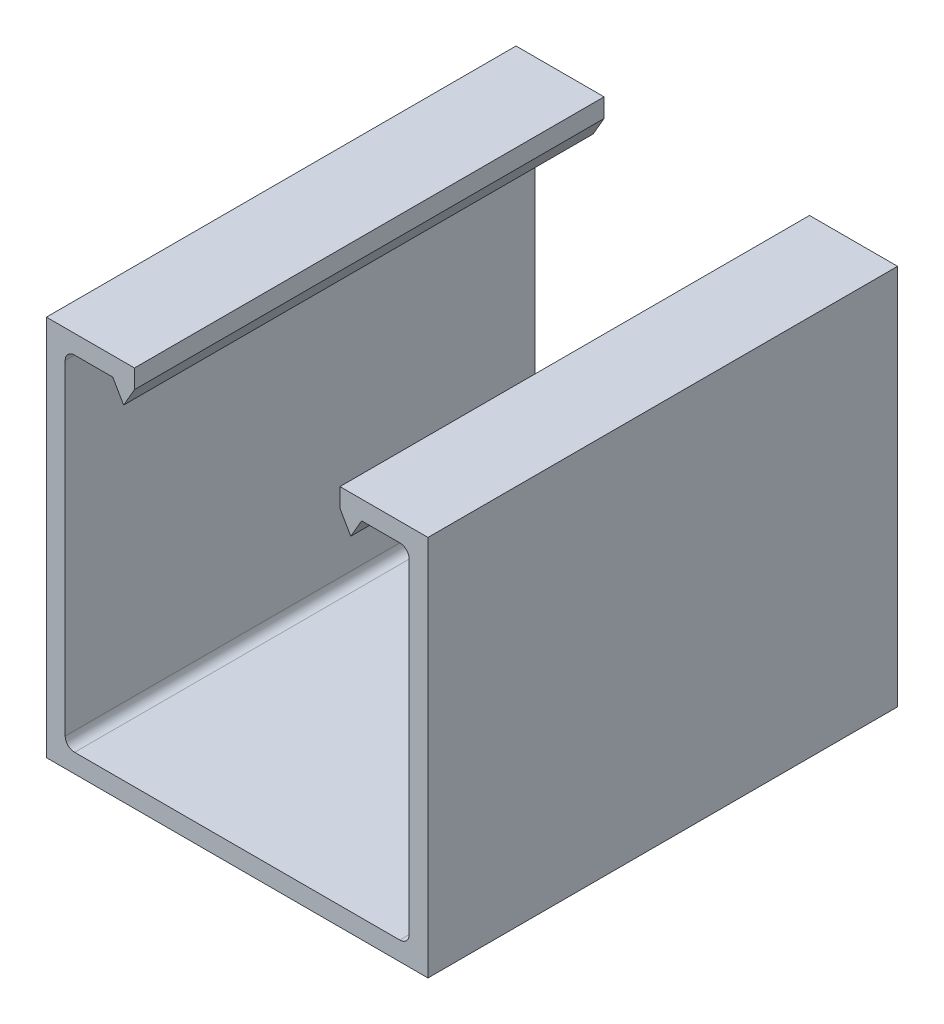
SolidWorks part; units mm, degrees
ref_plane "Plane1" through (0, 0, 0) normal (0, 0, 1) x (1, 0, 0)
ref_plane "Plane2" through (0, 0, 0) normal (0, 1, 0) x (1, 0, 0)
ref_plane "Plane3" through (0, 0, 0) normal (1, 0, 0) x (0, 0, -1)
sketch "Sketch1" plane through (0, 0, 0) normal (0, 0, 1) x (1, 0, 0)
  line L0 (-5.5563, 10.3187) -> (-10.3188, 10.3187)
  line L1 (-10.3188, 10.3187) -> (-10.3187, -10.3187)
  line L2 (-10.3187, -10.3187) -> (10.3188, -10.3187)
  line L3 (10.3188, -10.3187) -> (10.3187, 10.3188)
  line L4 (10.3187, 10.3188) -> (5.5562, 10.3188)
  line L5 (8.7948, 9.3028) -> (6.7294, 9.3028)
  line L6 (9.3028, -8.7948) -> (9.3027, 8.7948)
  line L7 (-8.7947, -9.3028) -> (8.7948, -9.3028)
  line L8 (-9.3027, 8.7947) -> (-9.3027, -8.7948)
  line L9 (-6.7294, 9.3027) -> (-8.7948, 9.3027)
  line L10 (6.7294, 9.3028) -> (6.1428, 8.2868)
  line L11 (6.1428, 8.2868) -> (5.5562, 9.3028)
  line L12 (5.5562, 9.3028) -> (5.5562, 10.3188)
  line L13 (-6.7294, 9.3027) -> (-6.1428, 8.2868)
  line L14 (-6.1428, 8.2868) -> (-5.5563, 9.3027)
  line L15 (-5.5563, 9.3027) -> (-5.5563, 10.3187)
  arc A0 (-9.3027, -8.7948) -> (-8.7947, -9.3028) centre (-8.7947, -8.7948) ccw
  arc A1 (-8.7948, 9.3027) -> (-9.3027, 8.7947) centre (-8.7948, 8.7947) ccw
  arc A2 (9.3027, 8.7948) -> (8.7948, 9.3028) centre (8.7948, 8.7948) ccw
  arc A3 (8.7948, -9.3028) -> (9.3028, -8.7948) centre (8.7948, -8.7948) ccw
  dimension "D5" = 0.508
  dimension "Width" = 20.6375
  dimension "Height" = 20.6375
  dimension "D8" = 10.3187
  dimension "D9" = 10.3187
  dimension "D10" = 11.1125
  dimension "edge" = 4.7625
  dimension "D13" = 0.5866
  dimension "D4" = 60
extrude "Base-Extrude" add sketch "Sketch1" along normal mid plane 25.4
equation "\"D8@Sketch1\" = \"Width@Sketch1\" / 2"
equation "\"D9@Sketch1\" = \"Height@Sketch1\" / 2"
equation "\"D10@Sketch1\" = \"Width@Sketch1\" - 2 * \"edge@Sketch1\""
equation "\"D5@Sketch1\" = \"gauge@Sketch1\" / 2"
equation "\"D13@Sketch1\" = \"gauge@Sketch1\" * .577350269"
